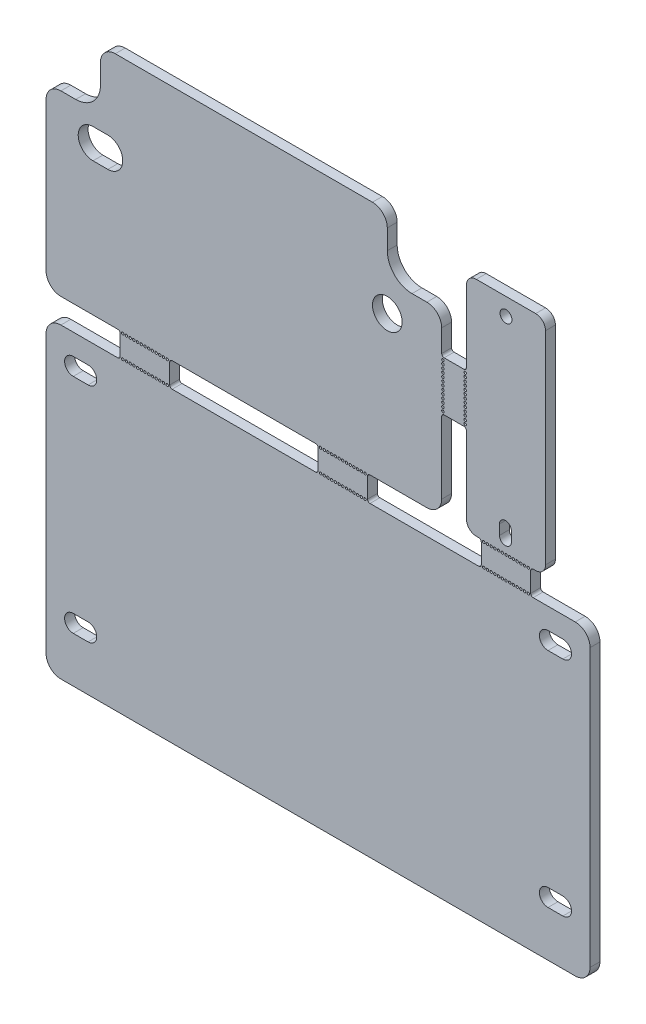
SolidWorks part; units mm, degrees
ref_plane "正面" through (0, 0, 0) normal (0, 0, 1) x (1, 0, 0)
ref_plane "平面" through (0, 0, 0) normal (0, 1, 0) x (1, 0, 0)
ref_plane "右側面" through (0, 0, 0) normal (1, 0, 0) x (0, 0, -1)
sketch "ｽｹｯﾁ1" plane through (0, 0, 0) normal (0, 0, 1) x (1, 0, 0)
  line L0 (-49.5, 24.75) -> (-46.5, 24.75)
  line L1 (55, 32.5) -> (-55, 32.5)
  line L2 (55, 32.5) -> (55, -32.5)
  line L3 (55, -32.5) -> (-55, -32.5)
  line L4 (-55, 32.5) -> (-55, -32.5)
  line L5 (55, 32.5) -> (-55, -32.5) construction
  line L6 (55, -32.5) -> (-55, 32.5) construction
  line L7 (-46.5, 28.25) -> (-49.5, 28.25)
  line L8 (-46.5, 28.25) -> (-46.5, 24.75) construction
  line L10 (-49.5, 28.25) -> (-49.5, 24.75) construction
  line L11 (-46.5, 28.25) -> (-49.5, 24.75) construction
  line L12 (-46.5, 24.75) -> (-49.5, 28.25) construction
  line L13 (-55, 4) -> (55, 4) construction
  line L14 (0, 32.5) -> (0, -32.5) construction
  line L15 (-46.5, -20.25) -> (-49.5, -20.25)
  line L16 (-49.5, -16.75) -> (-46.5, -16.75)
  line L17 (46.5, -20.25) -> (49.5, -20.25)
  line L18 (49.5, -16.75) -> (46.5, -16.75)
  line L19 (46.5, 28.25) -> (49.5, 28.25)
  line L20 (49.5, 24.75) -> (46.5, 24.75)
  arc A2 (-49.5, 28.25) -> (-49.5, 24.75) centre (-49.5, 26.5) ccw
  arc A3 (-46.5, 28.25) -> (-46.5, 24.75) centre (-46.5, 26.5) cw
  arc A4 (-49.5, -20.25) -> (-49.5, -16.75) centre (-49.5, -18.5) cw
  arc A5 (-46.5, -20.25) -> (-46.5, -16.75) centre (-46.5, -18.5) ccw
  arc A6 (46.5, -20.25) -> (46.5, -16.75) centre (46.5, -18.5) cw
  arc A7 (49.5, -20.25) -> (49.5, -16.75) centre (49.5, -18.5) ccw
  arc A8 (49.5, 28.25) -> (49.5, 24.75) centre (49.5, 26.5) cw
  arc A9 (46.5, 28.25) -> (46.5, 24.75) centre (46.5, 26.5) ccw
  point P0 (0, 0)
  point P6 (-48, 26.5)
  dimension "D3" = 3.5
  dimension "D4" = 3
  dimension "D1" = 65
  dimension "D2" = 110
  dimension "D5" = 6
  dimension "D6" = 7
  dimension "D7" = 22.5
extrude "ﾎﾞｽ - 押し出し1" add sketch "ｽｹｯﾁ1" along normal blind 2
fillet "ﾌｨﾚｯﾄ1" radius 3 2 edges at (55, 32.5, 1) (-55, 32.5, 1)
sketch "ｽｹｯﾁ2" plane through (0, 0, 2) normal (0, 0, 1) x (1, 0, 0)
  line L0 (-45.5, 64.5) -> (-42.5, 64.5)
  line L2 (-55, 85.5) -> (-55, 37.5) construction
  line L3 (-55, 37.5) -> (25, 37.5) construction
  line L4 (25, 85.5) -> (25, 37.5) construction
  line L5 (-55, 85.5) -> (25, 37.5) construction
  line L6 (-55, 37.5) -> (25, 85.5) construction
  line L7 (-45.5, 70.5) -> (-42.5, 70.5)
  line L8 (-45.5, 70.5) -> (-45.5, 64.5) construction
  line L10 (-42.5, 70.5) -> (-42.5, 64.5) construction
  line L11 (-45.5, 70.5) -> (-42.5, 64.5) construction
  line L12 (-45.5, 64.5) -> (-42.5, 70.5) construction
  line L17 (-44, 67.5) -> (14, 67.5) construction
  line L18 (-15, 85.5) -> (-15, 37.5) construction
  line L24 (-55, 85.5) -> (25, 85.5) construction
  line L25 (-55, 37.5) -> (25, 37.5)
  line L26 (25, 37.5) -> (25, 73.5)
  line L27 (25, 73.5) -> (14, 73.5)
  line L28 (14, 73.5) -> (14, 85.5)
  line L29 (14, 85.5) -> (-44, 85.5)
  line L30 (-44, 73.5) -> (-44, 85.5)
  line L31 (-55, 73.5) -> (-44, 73.5)
  line L32 (-55, 37.5) -> (-55, 73.5)
  line L33 (-55, 29.5) -> (-55, -32.5) construction
  line L34 (52, 32.5) -> (-52, 32.5) construction
  arc A0 (-45.5, 70.5) -> (-45.5, 64.5) centre (-45.5, 67.5) ccw
  arc A1 (-42.5, 70.5) -> (-42.5, 64.5) centre (-42.5, 67.5) cw
  circle A2 centre (14, 67.5) radius 3
  point P0 (-15, 61.5)
  point P5 (-44, 67.5)
  dimension "D6" = 6
  dimension "D7" = 29
  dimension "D1" = 80
  dimension "D2" = 48
  dimension "D3" = 6
  dimension "D4" = 3
  dimension "D5" = 29
  dimension "D8" = 12
  dimension "D9" = 11
  dimension "D10" = 18
  dimension "D11" = 5
extrude "ﾎﾞｽ - 押し出し2" add sketch "ｽｹｯﾁ2" against normal blind 2 separate body
fillet "ﾌｨﾚｯﾄ5" radius 3 6 edges at (-44, 85.5, 1) (-55, 73.5, 1) (14, 85.5, 1) (25, 73.5, 1) (25, 37.5, 1) (-55, 37.5, 1)
fillet "ﾌｨﾚｯﾄ6" radius 5 2 edges at (14, 73.5, 1) (-44, 73.5, 1)
sketch "ｽｹｯﾁ4" plane through (0, 0, 2) normal (0, 0, 1) x (1, 0, 0)
  line L0 (-40, 37.5) -> (-40, 32.5)
  line L1 (-52, 37.5) -> (22, 37.5) construction
  line L2 (52, 32.5) -> (-52, 32.5) construction
  line L3 (-40, 32.5) -> (-30, 32.5)
  line L4 (-30, 32.5) -> (-30, 37.5)
  line L5 (-30, 37.5) -> (-40, 37.5)
  line L6 (0, 37.5) -> (0, 32.5)
  line L7 (0, 32.5) -> (10, 32.5)
  line L8 (10, 32.5) -> (10, 37.5)
  line L9 (10, 37.5) -> (0, 37.5)
  line L10 (-55, 70.5) -> (-55, 40.5) construction
  line L11 (25, 40.5) -> (25, 70.5) construction
  dimension "D1" = 10
  dimension "D2" = 10
  dimension "D3" = 15
  dimension "D4" = 15
extrude "ﾎﾞｽ - 押し出し4" add sketch "ｽｹｯﾁ4" against normal blind 2
fillet "ﾌｨﾚｯﾄ7" radius 0.5 8 edges at (10, 37.5, 1) (10, 32.5, 1) (0, 37.5, 1) (0, 32.5, 1) (-30, 37.5, 1) (-30, 32.5, 1) (-40, 37.5, 1) (-40, 32.5, 1)
sketch "ｽｹｯﾁ5" plane through (0, 0, 2) normal (0, 0, 1) x (1, 0, 0)
  line L0 (36.6832, 42) -> (36.6832, 40)
  line L1 (30, 82.5) -> (46, 82.5)
  line L2 (30, 82.5) -> (30, 37.5)
  line L3 (30, 37.5) -> (46, 37.5)
  line L4 (46, 82.5) -> (46, 37.5)
  line L5 (30, 82.5) -> (46, 37.5) construction
  line L6 (30, 37.5) -> (46, 82.5) construction
  line L7 (39.0832, 42) -> (36.6832, 42) construction
  line L8 (39.0832, 42) -> (39.0832, 40)
  line L9 (39.0832, 40) -> (36.6832, 40) construction
  line L11 (39.0832, 42) -> (36.6832, 40) construction
  line L12 (39.0832, 40) -> (36.6832, 42) construction
  line L13 (25, 40.5) -> (25, 70.5) construction
  line L14 (52, 32.5) -> (10.5, 32.5) construction
  circle A0 centre (38, 79) radius 1.2
  arc A1 (36.6832, 42) -> (39.0832, 42) centre (37.8832, 42) cw
  arc A2 (39.0832, 40) -> (36.6832, 40) centre (37.8832, 40) cw
  point P0 (38, 60)
  point P7 (37.8832, 41)
  dimension "D3" = 2.4
  dimension "D1" = 45
  dimension "D2" = 16
  dimension "D4" = 2.4
  dimension "D5" = 2
  dimension "D6" = 19
  dimension "D7" = 19
  dimension "D8" = 5
  dimension "D9" = 5
extrude "ﾎﾞｽ - 押し出し5" add sketch "ｽｹｯﾁ5" against normal blind 2 separate body
sketch "ｽｹｯﾁ6" plane through (0, 0, 2) normal (0, 0, 1) x (1, 0, 0)
  line L0 (33, 37.5) -> (33, 32.5)
  line L1 (30, 37.5) -> (46, 37.5) construction
  line L2 (52, 32.5) -> (10.5, 32.5) construction
  line L3 (33, 32.5) -> (43, 32.5)
  line L4 (43, 32.5) -> (43, 37.5)
  line L5 (43, 37.5) -> (33, 37.5)
  line L6 (25, 65.5) -> (30, 65.5)
  line L7 (25, 40.5) -> (25, 70.5) construction
  line L8 (30, 82.5) -> (30, 37.5) construction
  line L9 (30, 65.5) -> (30, 55.5)
  line L10 (30, 55.5) -> (25, 55.5)
  line L11 (25, 55.5) -> (25, 65.5)
  line L13 (10.5, 37.5) -> (22, 37.5) construction
  dimension "D1" = 10
  dimension "D2" = 10
  dimension "D3" = 3
  dimension "D4" = 18
extrude "ﾎﾞｽ - 押し出し6" add sketch "ｽｹｯﾁ6" against normal blind 2
fillet "ﾌｨﾚｯﾄ8" radius 0.5 8 edges at (43, 32.5, 1) (43, 37.5, 1) (33, 32.5, 1) (33, 37.5, 1) (30, 55.5, 1) (25, 55.5, 1) (25, 65.5, 1) (30, 65.5, 1)
fillet "ﾌｨﾚｯﾄ9" radius 2 4 edges at (46, 82.5, 1) (30, 82.5, 1) (46, 37.5, 1) (30, 37.5, 1)
sketch "ｽｹｯﾁ7" plane through (0, 0, 2) normal (0, 0, 1) x (1, 0, 0)
  line L0 (-55, -32.5) -> (55, -32.5)
  line L1 (55, -32.5) -> (55, -29.5)
  line L2 (55, -32.5) -> (55, 29.5) construction
  line L3 (55, -29.5) -> (-55, -29.5)
  line L4 (-55, 29.5) -> (-55, -32.5) construction
  line L5 (-55, -29.5) -> (-55, -32.5)
  dimension "D1" = 3
extrude "ｶｯﾄ - 押し出し1" cut sketch "ｽｹｯﾁ7" against normal blind 10
fillet "ﾌｨﾚｯﾄ10" radius 3 2 edges at (55, -29.5, 1) (-55, -29.5, 1)
sketch "ｽｹｯﾁ8" plane through (0, 0, 2) normal (0, 0, 1) x (1, 0, 0)
  line L0 (-40.5, 37.5) -> (-29.5, 37.5) construction
  line L1 (-40, 37.25) -> (-30, 37.25) construction
  line L2 (-40, 37) -> (-40, 33) construction
  line L3 (-30, 33) -> (-30, 37) construction
  line L4 (-40, 35) -> (-30, 35) construction
  line L5 (-15, 37.5) -> (-15, 32.5) construction
  line L6 (-29.5, 37.5) -> (-0.5, 37.5) construction
  line L7 (-0.5, 32.5) -> (-29.5, 32.5) construction
  line L8 (21.5, 32.5) -> (21.5, 37.5) construction
  line L9 (32.5, 32.5) -> (10.5, 32.5) construction
  line L10 (10.5, 37.5) -> (22, 37.5) construction
  circle A0 centre (-39.5, 37.25) radius 0.25
  circle A1 centre (-38.75, 37.25) radius 0.25
  circle A2 centre (-38, 37.25) radius 0.25
  circle A3 centre (-37.25, 37.25) radius 0.25
  circle A4 centre (-36.5, 37.25) radius 0.25
  circle A5 centre (-35.75, 37.25) radius 0.25
  circle A6 centre (-35, 37.25) radius 0.25
  circle A7 centre (-34.25, 37.25) radius 0.25
  circle A8 centre (-33.5, 37.25) radius 0.25
  circle A9 centre (-32.75, 37.25) radius 0.25
  circle A10 centre (-32, 37.25) radius 0.25
  circle A11 centre (-31.25, 37.25) radius 0.25
  circle A12 centre (-30.5, 37.25) radius 0.25
  circle A13 centre (-30.5, 32.75) radius 0.25
  circle A14 centre (-31.25, 32.75) radius 0.25
  circle A15 centre (-32, 32.75) radius 0.25
  circle A16 centre (-32.75, 32.75) radius 0.25
  circle A17 centre (-33.5, 32.75) radius 0.25
  circle A18 centre (-34.25, 32.75) radius 0.25
  circle A19 centre (-35, 32.75) radius 0.25
  circle A20 centre (-35.75, 32.75) radius 0.25
  circle A21 centre (-36.5, 32.75) radius 0.25
  circle A22 centre (-37.25, 32.75) radius 0.25
  circle A23 centre (-38, 32.75) radius 0.25
  circle A24 centre (-38.75, 32.75) radius 0.25
  circle A25 centre (-39.5, 32.75) radius 0.25
  circle A26 centre (0.5, 32.75) radius 0.25
  circle A27 centre (1.25, 32.75) radius 0.25
  circle A28 centre (2, 32.75) radius 0.25
  circle A29 centre (2.75, 32.75) radius 0.25
  circle A30 centre (3.5, 32.75) radius 0.25
  circle A31 centre (4.25, 32.75) radius 0.25
  circle A32 centre (5, 32.75) radius 0.25
  circle A33 centre (5.75, 32.75) radius 0.25
  circle A34 centre (6.5, 32.75) radius 0.25
  circle A35 centre (7.25, 32.75) radius 0.25
  circle A36 centre (8, 32.75) radius 0.25
  circle A37 centre (8.75, 32.75) radius 0.25
  circle A38 centre (9.5, 32.75) radius 0.25
  circle A39 centre (0.5, 37.25) radius 0.25
  circle A40 centre (1.25, 37.25) radius 0.25
  circle A41 centre (2, 37.25) radius 0.25
  circle A42 centre (2.75, 37.25) radius 0.25
  circle A43 centre (3.5, 37.25) radius 0.25
  circle A44 centre (4.25, 37.25) radius 0.25
  circle A45 centre (5, 37.25) radius 0.25
  circle A46 centre (5.75, 37.25) radius 0.25
  circle A47 centre (6.5, 37.25) radius 0.25
  circle A48 centre (7.25, 37.25) radius 0.25
  circle A49 centre (8, 37.25) radius 0.25
  circle A50 centre (8.75, 37.25) radius 0.25
  circle A51 centre (9.5, 37.25) radius 0.25
  circle A52 centre (33.5, 32.75) radius 0.25
  circle A53 centre (34.25, 32.75) radius 0.25
  circle A54 centre (35, 32.75) radius 0.25
  circle A55 centre (35.75, 32.75) radius 0.25
  circle A56 centre (36.5, 32.75) radius 0.25
  circle A57 centre (37.25, 32.75) radius 0.25
  circle A58 centre (38, 32.75) radius 0.25
  circle A59 centre (38.75, 32.75) radius 0.25
  circle A60 centre (39.5, 32.75) radius 0.25
  circle A61 centre (40.25, 32.75) radius 0.25
  circle A62 centre (41, 32.75) radius 0.25
  circle A63 centre (41.75, 32.75) radius 0.25
  circle A64 centre (42.5, 32.75) radius 0.25
  circle A65 centre (33.5, 37.25) radius 0.25
  circle A66 centre (34.25, 37.25) radius 0.25
  circle A67 centre (35, 37.25) radius 0.25
  circle A68 centre (35.75, 37.25) radius 0.25
  circle A69 centre (36.5, 37.25) radius 0.25
  circle A70 centre (37.25, 37.25) radius 0.25
  circle A71 centre (38, 37.25) radius 0.25
  circle A72 centre (38.75, 37.25) radius 0.25
  circle A73 centre (39.5, 37.25) radius 0.25
  circle A74 centre (40.25, 37.25) radius 0.25
  circle A75 centre (41, 37.25) radius 0.25
  circle A76 centre (41.75, 37.25) radius 0.25
  circle A77 centre (42.5, 37.25) radius 0.25
  dimension "D2" = 0.5
  dimension "D3" = 0.5
  dimension "D1" = 0.25
  dimension "D4" = 13
extrude "ｶｯﾄ - 押し出し2" cut sketch "ｽｹｯﾁ8" against normal blind 10
sketch "ｽｹｯﾁ9" plane through (0, 0, 2) normal (0, 0, 1) x (1, 0, 0)
  line L0 (25, 66) -> (25, 55) construction
  line L1 (25.25, 65.5) -> (25.25, 55.433) construction
  line L2 (29.5, 65.5) -> (25.5, 65.5) construction
  line L3 (25.5, 55.5) -> (29.5, 55.5) construction
  line L4 (27.5, 65.5) -> (27.5, 55.5) construction
  circle A0 centre (25.25, 56) radius 0.25
  arc A1 (25.5, 55.5) -> (25, 55) centre (25.5, 55) ccw construction
  circle A2 centre (25.25, 56.75) radius 0.25
  circle A3 centre (25.25, 57.5) radius 0.25
  circle A4 centre (25.25, 58.25) radius 0.25
  circle A5 centre (25.25, 59) radius 0.25
  circle A6 centre (25.25, 59.75) radius 0.25
  circle A7 centre (25.25, 60.5) radius 0.25
  circle A8 centre (25.25, 61.25) radius 0.25
  circle A9 centre (25.25, 62) radius 0.25
  circle A10 centre (25.25, 62.75) radius 0.25
  circle A11 centre (25.25, 63.5) radius 0.25
  circle A12 centre (25.25, 64.25) radius 0.25
  circle A13 centre (25.25, 65) radius 0.25
  circle A14 centre (29.75, 65) radius 0.25
  circle A15 centre (29.75, 64.25) radius 0.25
  circle A16 centre (29.75, 63.5) radius 0.25
  circle A17 centre (29.75, 62.75) radius 0.25
  circle A18 centre (29.75, 62) radius 0.25
  circle A19 centre (29.75, 61.25) radius 0.25
  circle A20 centre (29.75, 60.5) radius 0.25
  circle A21 centre (29.75, 59.75) radius 0.25
  circle A22 centre (29.75, 59) radius 0.25
  circle A23 centre (29.75, 58.25) radius 0.25
  circle A24 centre (29.75, 57.5) radius 0.25
  circle A25 centre (29.75, 56.75) radius 0.25
  circle A26 centre (29.75, 56) radius 0.25
  dimension "D2" = 0.5
  dimension "D3" = 0.5
  dimension "D1" = 0.25
  dimension "D4" = 13
extrude "ｶｯﾄ - 押し出し3" cut sketch "ｽｹｯﾁ9" against normal blind 10
